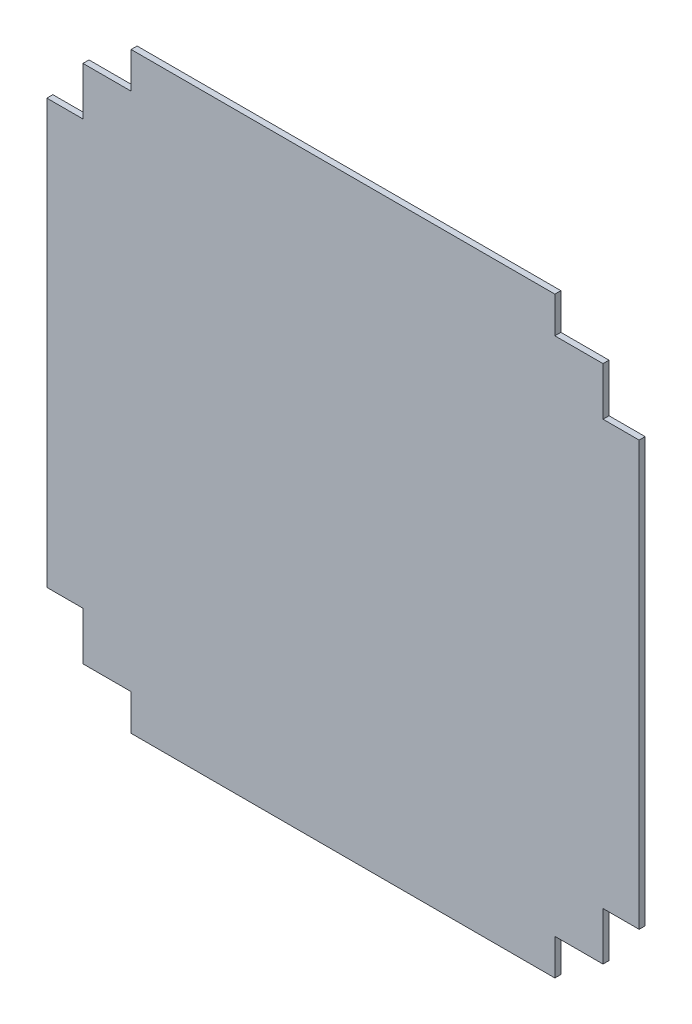
SolidWorks part; units mm, degrees
material "Acrílico (Impacto medio-alto)"
ref_plane "Alzado" through (0, 0, 0) normal (0, 0, 1) x (1, 0, 0)
ref_plane "Planta" through (0, 0, 0) normal (0, 1, 0) x (1, 0, 0)
ref_plane "Vista lateral" through (0, 0, 0) normal (1, 0, 0) x (0, 0, -1)
sketch "Croquis1" plane through (0, 0, 0) normal (0, 0, 1) x (1, 0, 0)
  line L0 (-246, 0) -> (246, 0)
  line L1 (0, 0) -> (0, 246) construction
  line L2 (-246, -176) -> (-246, 176)
  line L3 (-246, 176) -> (-216, 176)
  line L4 (-216, 176) -> (-216, 216)
  line L5 (-216, 216) -> (-176, 216)
  line L6 (-176, 216) -> (-176, 246)
  line L7 (-176, 246) -> (176, 246)
  line L8 (246, -176) -> (246, 176)
  line L9 (246, 176) -> (216, 176)
  line L10 (216, 176) -> (216, 216)
  line L11 (216, 216) -> (176, 216)
  line L12 (176, 216) -> (176, 246)
  line L13 (-246, -176) -> (-216, -176)
  line L14 (-216, -176) -> (-216, -216)
  line L15 (-216, -216) -> (-176, -216)
  line L16 (-176, -216) -> (-176, -246)
  line L17 (-176, -246) -> (176, -246)
  line L18 (176, -216) -> (176, -246)
  line L19 (216, -216) -> (176, -216)
  line L20 (216, -176) -> (216, -216)
  line L21 (246, -176) -> (216, -176)
  point P4 (0, 0)
  dimension "D1" = 492
  dimension "D2" = 176
  dimension "D3" = 216
  dimension "D4" = 176
  dimension "D5" = 30
  dimension "D6" = 40
extrude "Saliente-Extruir1" add sketch "Croquis1" along normal blind 5 contours L1 L0 L8 L9 L10 L11 L12 L7 | L0 L1 L7 L6 L5 L4 L3 L2 | L21 L8 L0 L2 L13 L14 L15 L16 L17 L18 L19 L20
